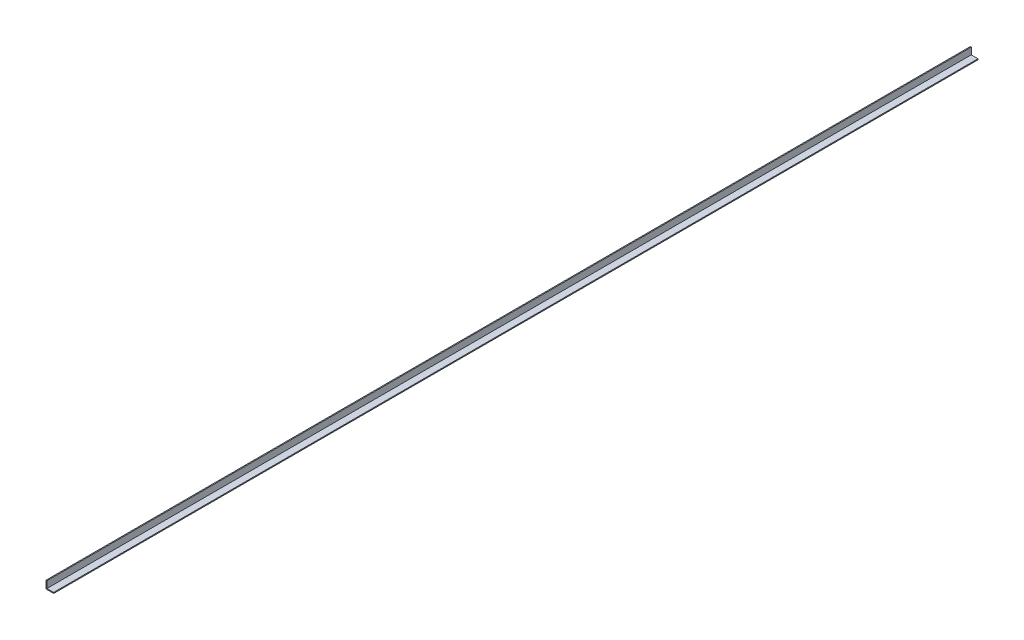
SolidWorks part; units mm, degrees
material "ASTM A36 Acero"
ref_plane "Alzado" through (0, 0, 0) normal (0, 0, 1) x (1, 0, 0)
ref_plane "Planta" through (0, 0, 0) normal (0, 1, 0) x (1, 0, 0)
ref_plane "Vista lateral" through (0, 0, 0) normal (1, 0, 0) x (0, 0, -1)
sketch "Croquis1" plane through (0, 0, 0) normal (0, 0, 1) x (1, 0, 0)
  line L0 (0, 50.8) -> (0, 0)
  line L1 (0, 0) -> (50.8, 0)
  line L2 (50.8, 0) -> (50.8, 6.35)
  line L3 (50.8, 6.35) -> (6.35, 6.35)
  line L4 (6.35, 6.35) -> (6.35, 50.8)
  line L5 (6.35, 50.8) -> (0, 50.8)
  dimension "D1" = 6.35
  dimension "D2" = 50.8
extrude "Saliente-Extruir1" add sketch "Croquis1" against normal blind 6100
